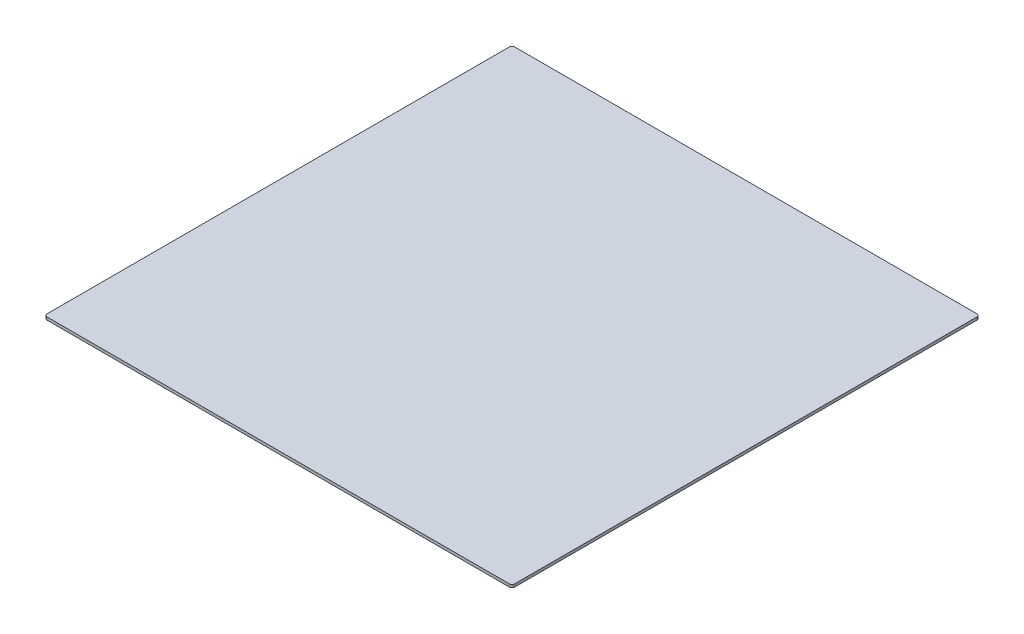
SolidWorks part; units mm, degrees
material "Glass"
ref_plane "Front Plane" through (0, 0, 0) normal (0, 0, 1) x (1, 0, 0)
ref_plane "Top Plane" through (0, 0, 0) normal (0, 1, 0) x (1, 0, 0)
ref_plane "Right Plane" through (0, 0, 0) normal (1, 0, 0) x (0, 0, -1)
sketch "Sketch1" plane through (0, 0, 0) normal (0, 1, 0) x (1, 0, 0)
  line L1 (-250, 250) -> (250, 250)
  line L2 (-250, 250) -> (-250, -250)
  line L3 (-250, -250) -> (250, -250)
  line L4 (250, 250) -> (250, -250)
  line L5 (-250, 250) -> (250, -250) construction
  line L6 (-250, -250) -> (250, 250) construction
  point P0 (0, 0)
  dimension "D1" = 500
extrude "Boss-Extrude1" add sketch "Sketch1" along normal blind 3
fillet "Fillet1" radius 3 4 edges at (-250, 1.5, 250) (-250, 1.5, -250) (250, 1.5, -250) (250, 1.5, 250)
